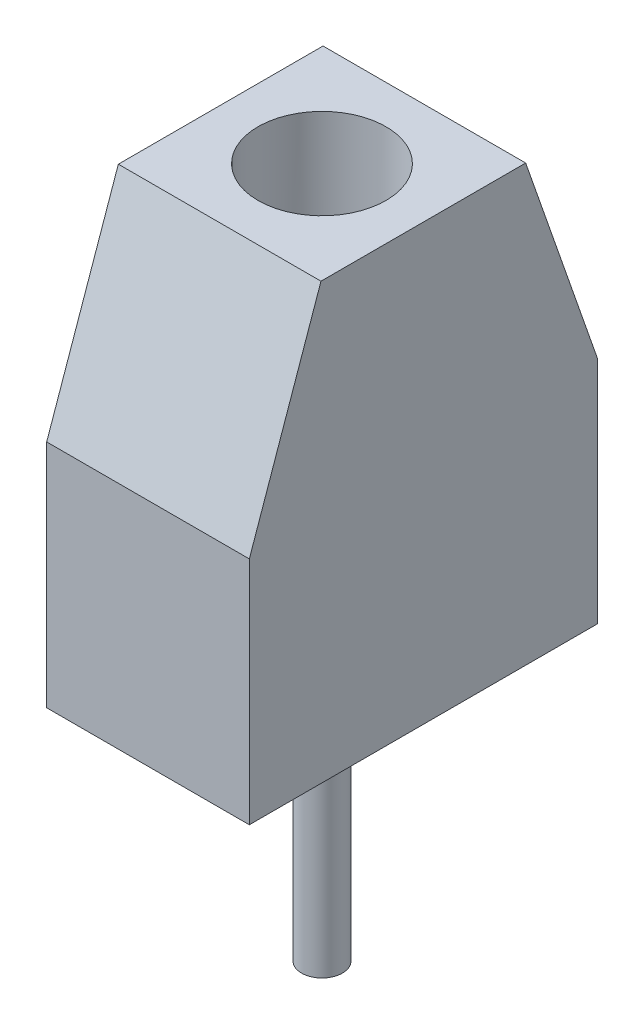
SolidWorks part; units mm, degrees
ref_plane "前视基准面" through (0, 0, 0) normal (0, 0, 1) x (1, 0, 0)
ref_plane "上视基准面" through (0, 0, 0) normal (0, 1, 0) x (1, 0, 0)
ref_plane "右视基准面" through (0, 0, 0) normal (1, 0, 0) x (0, 0, -1)
sketch "草图1" plane through (0, 0, 0) normal (1, 0, 0) x (0, 0, -1)
  line L0 (0, 62.0908) -> (0, -32.2364) construction
  line L1 (3.4, 0) -> (-3.4, 0)
  line L2 (-3.4, 0) -> (-3.4, 4.5)
  line L3 (-3.4, 4.5) -> (-2, 8.5)
  line L4 (-2, 8.5) -> (2, 8.5)
  line L5 (3.4, 4.5) -> (2, 8.5)
  line L6 (3.4, 0) -> (3.4, 4.5)
  point P9 (0, 8.5)
  point P11 (0, 0)
  dimension "D1" = 8.5
  dimension "D2" = 4.5
  dimension "D3" = 6.8
  dimension "D4" = 4
extrude "凸台-拉伸1" add sketch "草图1" along normal blind 3.96
sketch "草图3" plane through (0, 8.5, 0) normal (0, 1, 0) x (1, 0, 0)
  line L0 (1.98, 4.7919) -> (1.98, -5.08) construction
  line L1 (-1.7268, 0) -> (6.8583, 0) construction
  line L2 (0, 2) -> (0, -2) construction
  line L3 (3.96, 2) -> (3.96, -2) construction
  circle A0 centre (1.98, 0) radius 1.25
  dimension "D1" = 2.5
extrude "切除-拉伸1" cut sketch "草图3" against normal blind 2
sketch "草图4" plane through (0, 6.5, 0) normal (0, 1, 0) x (1, 0, 0)
  line L0 (0.7553, 0.25) -> (3.2047, 0.25)
  line L1 (-0.5324, 0) -> (4.1422, 0) construction
  line L2 (0.7553, -0.25) -> (3.2047, -0.25)
  circle A0 centre (1.98, 0) radius 1.25 construction
  arc A1 (0.7553, 0.25) -> (0.7553, -0.25) centre (1.98, 0) ccw
  arc A4 (3.2047, -0.25) -> (3.2047, 0.25) centre (1.98, 0) ccw
  dimension "D1" = 0.5
extrude "切除-拉伸2" cut sketch "草图4" against normal blind 0.5
sketch "草图5" plane through (0, 0, 0) normal (0, -1, 0) x (1, 0, 0)
  line L0 (-1.4211, 0) -> (5.6923, 0) construction
  line L1 (1.98, 3.6512) -> (1.98, -3.7849) construction
  line L2 (0, 3.4) -> (0, -3.4) construction
  line L3 (3.96, 3.4) -> (3.96, -3.4) construction
  circle A0 centre (1.98, 0) radius 0.4
  dimension "D1" = 0.8
extrude "凸台-拉伸2" add sketch "草图5" along normal blind 5
